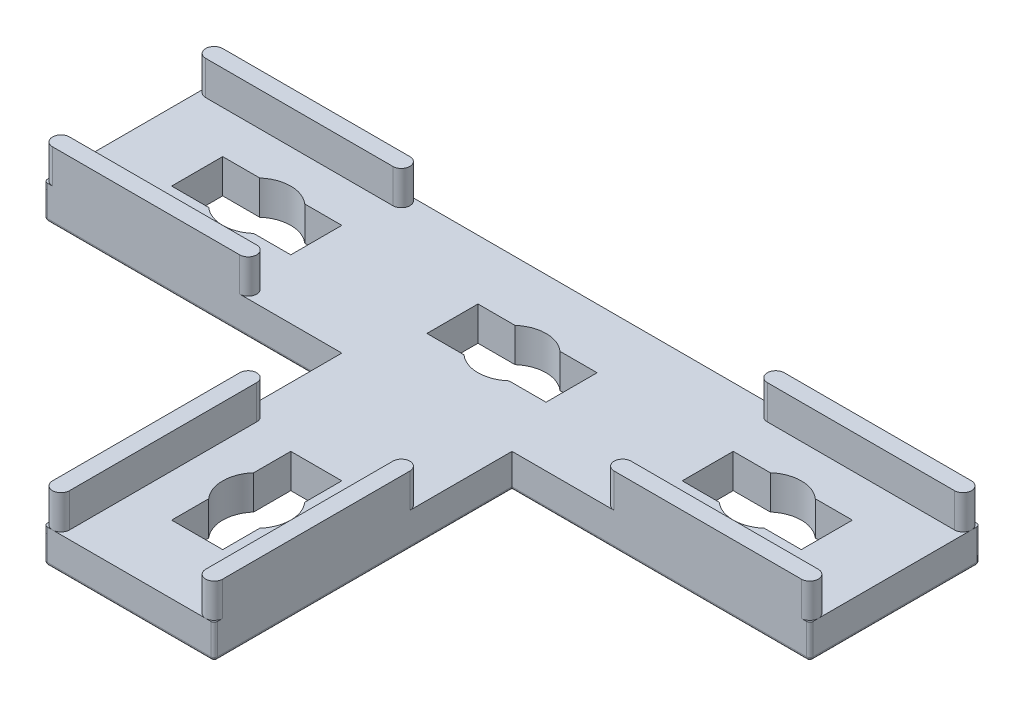
SolidWorks part; units mm, degrees
ref_plane "前视基准面" through (0, 0, 0) normal (0, 0, 1) x (1, 0, 0)
ref_plane "上视基准面" through (0, 0, 0) normal (0, 1, 0) x (1, 0, 0)
ref_plane "右视基准面" through (0, 0, 0) normal (1, 0, 0) x (0, 0, -1)
sketch "草图1" plane through (0, 0, 0) normal (0, 1, 0) x (1, 0, 0)
  line L0 (22.5, 5) -> (22.5, -5)
  line L1 (22.5, 5) -> (-22.5, 5)
  line L2 (22.5, -5) -> (5, -5)
  line L3 (-22.5, 5) -> (-22.5, -5)
  line L4 (22.5, 5) -> (-22.5, -5) construction
  line L5 (22.5, -5) -> (-22.5, 5) construction
  line L6 (0, 0) -> (-5, 0) construction
  line L7 (-5, -5) -> (-22.5, -5)
  line L8 (-5, -22.5) -> (5, -22.5)
  line L9 (5, -22.5) -> (5, -5)
  line L10 (5, 0) -> (0, 0) construction
  line L11 (-5, -5) -> (-5, -22.5)
  point P1 (0, 0)
  dimension "D1" = 10
  dimension "D2" = 45
  dimension "D3" = 5
  dimension "D4" = 5
  dimension "D5" = 22.5
  dimension "D6" = 5
  dimension "D7" = 10
extrude "凸台-拉伸1" add sketch "草图1" along normal blind 2
sketch "草图2" plane through (0, 2, 0) normal (0, 1, 0) x (1, 0, 0)
  line L0 (-22.5, 5) -> (-22.5, 4.5) construction
  line L2 (-22.5, 5) -> (-22.5, -5) construction
  line L5 (-22, 4) -> (-11, 4)
  line L7 (-22, 5) -> (-11, 5)
  arc A0 (-22, 5) -> (-22, 4) centre (-22, 4.5) ccw
  arc A1 (-11, 4) -> (-11, 5) centre (-11, 4.5) ccw
extrude "凸台-拉伸2" add sketch "草图2" along normal blind 2
mirror "镜向1" about plane through (0, 0, 0) normal (0, 0, 1) of "凸台-拉伸2"
pattern_linear "阵列(线性)1" count 2 spacing 33 along (1, 0, 0) of "镜向1", "凸台-拉伸2"
sketch "草图3" plane through (0, 2, 0) normal (0, 1, 0) x (1, 0, 0)
  line L0 (-5, -22.5) -> (-4.5, -22.5) construction
  line L1 (-5, -22.5) -> (5, -22.5) construction
  line L2 (-4.5, -22.5) -> (-4.5, -22) construction
  line L4 (-4, -22) -> (-4, -11)
  line L5 (-5, -22) -> (-5, -11)
  arc A0 (-5, -22) -> (-4, -22) centre (-4.5, -22) ccw
  arc A1 (-5, -11) -> (-4, -11) centre (-4.5, -11) cw
extrude "凸台-拉伸3" add sketch "草图3" along normal blind 2
mirror "镜向2" about plane through (0, 0, 0) normal (1, 0, 0) of "凸台-拉伸3"
sketch "草图4" plane through (0, 2, 0) normal (0, 1, 0) x (1, 0, 0)
  line L0 (3.5, 1.5) -> (3.5, -1.5)
  line L1 (3.5, 1.5) -> (1.3229, 1.5)
  line L2 (3.5, -1.5) -> (1.3229, -1.5)
  line L3 (-3.5, 1.5) -> (-3.5, -1.5)
  line L4 (3.5, 1.5) -> (-3.5, -1.5) construction
  line L5 (3.5, -1.5) -> (-3.5, 1.5) construction
  line L6 (-1.3229, 1.5) -> (-3.5, 1.5)
  line L7 (-1.3229, -1.5) -> (-3.5, -1.5)
  arc A0 (-1.3229, -1.5) -> (1.3229, -1.5) centre (0, 0) ccw
  arc A1 (1.3229, 1.5) -> (-1.3229, 1.5) centre (0, 0) ccw
  dimension "D1" = 4
  dimension "D2" = 3
  dimension "D3" = 7
extrude "切除-拉伸1" cut sketch "草图4" against normal up to next
pattern_linear "阵列(线性)2" count 2 spacing 15 along (1, 0, 0) count 2 spacing 15 along (-1, 0, 0) of "切除-拉伸1"
sketch "草图5" plane through (0, 2, 0) normal (0, 1, 0) x (1, 0, 0)
  line L0 (0, -22.5) -> (0, -15) construction
  line L1 (-4.5, -22.5) -> (4.5, -22.5) construction
  line L2 (1.5, -11.5) -> (-1.5, -11.5)
  line L3 (1.5, -11.5) -> (1.5, -13.6771)
  line L4 (-1.5, -11.5) -> (-1.5, -13.6771)
  line L5 (1.5, -18.5) -> (-1.5, -18.5)
  line L6 (1.5, -11.5) -> (-1.5, -18.5) construction
  line L7 (-1.5, -11.5) -> (1.5, -18.5) construction
  line L8 (-1.5, -16.3229) -> (-1.5, -18.5)
  line L9 (1.5, -16.3229) -> (1.5, -18.5)
  arc A0 (-1.5, -13.6771) -> (-1.5, -16.3229) centre (0, -15) ccw
  arc A1 (1.5, -16.3229) -> (1.5, -13.6771) centre (0, -15) ccw
  dimension "D2" = 4
  dimension "D1" = 7.5
  dimension "D3" = 3
  dimension "D4" = 7
extrude "切除-拉伸2" cut sketch "草图5" against normal up to next
fillet "圆角1" radius 0.2 14 edges at (22.5, 1, 5) (22.5, 1, -5) (-22.5, 1, -5) (-22.5, 1, 5) (5, 1, 22.5) (-5, 1, 22.5) (-22.5, 0, 0) (22.5, 0, 0) (0, 0, 22.5) (5, 0, 13.75) (-5, 0, 13.75) (-13.75, 0, 5) (13.75, 0, 5) (0, 0, -5)
